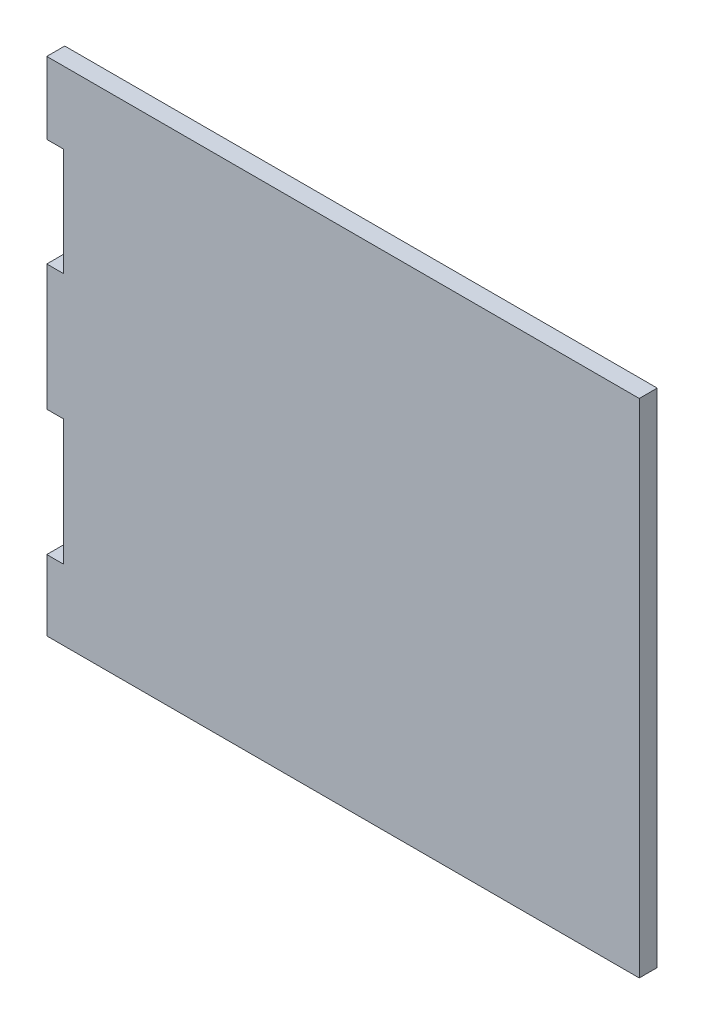
SolidWorks part; units mm, degrees
ref_plane "Front Plane" through (0, 0, 0) normal (0, 0, 1) x (1, 0, 0)
ref_plane "Top Plane" through (0, 0, 0) normal (0, 1, 0) x (1, 0, 0)
ref_plane "Right Plane" through (0, 0, 0) normal (1, 0, 0) x (0, 0, -1)
sketch "Model" plane through (0, 0, 0) normal (0, 0, 1) x (1, 0, 0)
  line L0 (104.434, 94.6585) -> (-104.8687, 94.6585)
  line L1 (-104.8687, 94.6585) -> (-104.8687, 69.2585)
  line L2 (-104.8687, 69.2585) -> (-99.0122, 69.2585)
  line L3 (-99.0122, 69.2585) -> (-99.0122, 31.1585)
  line L4 (-99.0122, 31.1585) -> (-104.8687, 31.1585)
  line L5 (-104.8687, 31.1585) -> (-104.8687, -13.2915)
  line L6 (-104.8687, -13.2915) -> (-99.0122, -13.2915)
  line L7 (-99.0122, -13.2915) -> (-99.0122, -57.7414)
  line L8 (-99.0122, -57.7414) -> (-104.8687, -57.7414)
  line L9 (-104.8687, -57.7414) -> (-104.8687, -82.6482)
  line L10 (-104.8687, -82.6482) -> (104.434, -82.6482)
  line L11 (104.434, -82.6482) -> (104.434, 94.6585)
extrude "Boss-Extrude1" add sketch "Model" along normal blind 6.35 contours L0 L1 L2 L3 L4 L5 L6 L7 L8 L9 L10 L11
